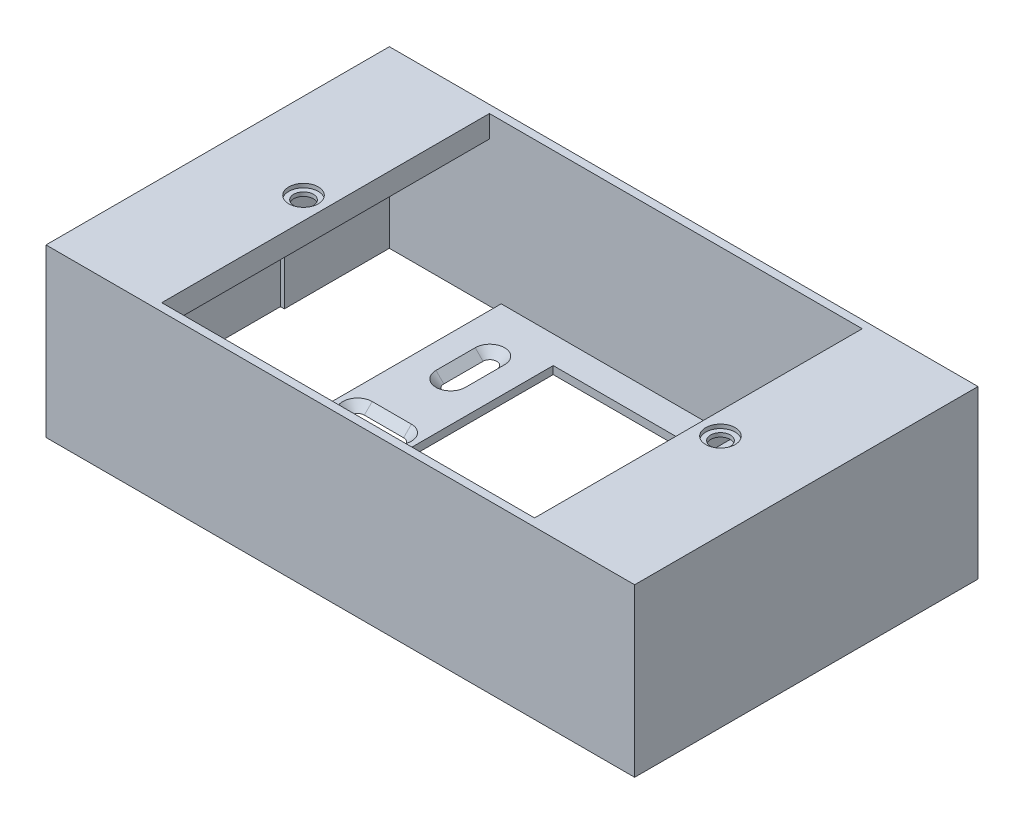
SolidWorks part; units mm, degrees
ref_plane "Front Plane" through (0, 0, 0) normal (0, 0, 1) x (1, 0, 0)
ref_plane "Top Plane" through (0, 0, 0) normal (0, 1, 0) x (1, 0, 0)
ref_plane "Right Plane" through (0, 0, 0) normal (1, 0, 0) x (0, 0, -1)
sketch "Sketch1" plane through (0, 0, 0) normal (0, 1, 0) x (1, 0, 0)
  line L1 (-60, -35) -> (60, -35)
  line L2 (-60, -35) -> (-60, 35)
  line L3 (-60, 35) -> (60, 35)
  line L4 (60, -35) -> (60, 35)
  line L5 (-60, -35) -> (60, 35) construction
  line L6 (-60, 35) -> (60, -35) construction
  point P0 (0, 0)
  dimension "D1" = 120
  dimension "D2" = 70
extrude "Boss-Extrude1" add sketch "Sketch1" along normal blind 34
shell "Shell1" thickness 1.6
sketch "Sketch2" plane through (0, 34, 0) normal (0, 1, 0) x (1, 0, 0)
  line L0 (-60, 35) -> (-60, -35) construction
  line L1 (-38, -33.4) -> (38, -33.4)
  line L2 (-38, -33.4) -> (-38, 33.4)
  line L3 (-38, 33.4) -> (38, 33.4)
  line L4 (38, -33.4) -> (38, 33.4)
  line L5 (-38, -33.4) -> (38, 33.4) construction
  line L6 (-38, 33.4) -> (38, -33.4) construction
  line L7 (60, 35) -> (-60, 35) construction
  point P0 (0, 0)
  dimension "D1" = 22
  dimension "D2" = 1.6
extrude "Cut-Extrude1" cut sketch "Sketch2" against normal up to next
sketch "Sketch3" plane through (0, 34, 0) normal (0, 1, 0) x (1, 0, 0)
  line L0 (-60, 0) -> (60, 0) construction
  line L1 (-60, 35) -> (-60, -35) construction
  line L2 (60, -35) -> (60, 35) construction
  line L3 (60, 35) -> (-60, 35) construction
  line L4 (-39.6, -35) -> (-38, -35)
  line L5 (-39.6, -35) -> (-39.6, 35)
  line L6 (-39.6, 35) -> (-38, 35)
  line L7 (-38, -35) -> (-38, 35)
  line L8 (-39.6, -35) -> (-38, 35) construction
  line L9 (-39.6, 35) -> (-38, -35) construction
  line L10 (-38, 33.4) -> (-38, -33.4) construction
  point P6 (-38.8, 0)
  point P15 (0, 0)
  point P16 (0, 0)
  dimension "D1" = 1.6
extrude "Boss-Extrude2" add sketch "Sketch3" against normal blind 4.5
sketch "Sketch4" plane through (0, 34, 0) normal (0, 1, 0) x (1, 0, 0)
  line L0 (-60, 35) -> (-60, -35) construction
  circle A0 centre (-42.5, 0) radius 3
  point P2 (0, 0)
  dimension "D1" = 6
  dimension "D2" = 17.5
extrude "Cut-Extrude2" cut sketch "Sketch4" against normal blind 0.8
sketch "Sketch5" plane through (0, 34, 0) normal (0, 1, 0) x (1, 0, 0)
  circle A0 centre (-42.5, 0) radius 2
  dimension "D1" = 4
extrude "Cut-Extrude3" cut sketch "Sketch5" against normal up to next contours A0
mirror "Mirror1" about plane through (0, 0, 0) normal (1, 0, 0) of "Boss-Extrude2", "Cut-Extrude2", "Cut-Extrude3"
sketch "Sketch7" plane through (0, 0, 0) normal (0, 1, 0) x (1, 0, 0)
  line L0 (-58.4, -33.4) -> (58.4, -33.4) construction
  line L1 (-35.6, 33.4) -> (35.6, 33.4)
  line L2 (-35.6, 33.4) -> (-35.6, -33.4)
  line L3 (-35.6, -33.4) -> (35.6, -33.4)
  line L4 (35.6, 33.4) -> (35.6, -33.4)
  line L5 (-35.6, 33.4) -> (35.6, -33.4) construction
  line L6 (-35.6, -33.4) -> (35.6, 33.4) construction
  line L7 (-60, 35) -> (-60, -35) construction
  line L8 (-19.4, 27.8) -> (19.4, 27.8)
  line L9 (-19.4, 27.8) -> (-19.4, -27.8)
  line L10 (-19.4, -27.8) -> (19.4, -27.8)
  line L11 (19.4, 27.8) -> (19.4, -27.8)
  line L12 (-19.4, 27.8) -> (19.4, -27.8) construction
  line L13 (-19.4, -27.8) -> (19.4, 27.8) construction
  line L14 (-60, -35) -> (60, -35) construction
  point P0 (0, 0)
  point P8 (0, 0)
  dimension "D1" = 40.6
  dimension "D2" = 16.2
  dimension "D3" = 7.2
extrude "Boss-Extrude3" add sketch "Sketch7" along normal blind 1.6
sketch "Sketch8" plane through (0, 1.6, 0) normal (0, 1, 0) x (1, 0, 0)
  line L0 (-27.5, -33.4) -> (-27.5, 33.4) construction
  line L1 (-38, -33.4) -> (38, -33.4) construction
  line L2 (35.6, 33.4) -> (-35.6, 33.4) construction
  line L3 (27.5, -33.4) -> (27.5, 33.4) construction
  line L4 (-35.6, -33.4) -> (35.6, -33.4) construction
  line L5 (-35.6, 0) -> (35.6, 0) construction
  line L6 (-35.6, 33.4) -> (-35.6, -33.4) construction
  line L7 (35.6, -33.4) -> (35.6, 33.4) construction
  line L8 (-31.5, 0) -> (-23.5, 0) construction
  line L9 (-31.5, 3) -> (-23.5, 3)
  line L10 (-31.5, -3) -> (-23.5, -3)
  line L11 (27.5, -4) -> (27.5, 4) construction
  line L12 (24.5, -4) -> (24.5, 4)
  line L13 (30.5, -4) -> (30.5, 4)
  line L14 (-35.6, 19) -> (35.6, 19) construction
  line L15 (-35.6, -19) -> (35.6, -19) construction
  line L16 (60, 35) -> (-60, 35) construction
  line L17 (-60, -35) -> (60, -35) construction
  line L18 (23.5, 19) -> (31.5, 19) construction
  line L19 (23.5, 22) -> (31.5, 22)
  line L20 (23.5, 16) -> (31.5, 16)
  line L21 (23.5, -19) -> (31.5, -19) construction
  line L22 (23.5, -16) -> (31.5, -16)
  line L23 (23.5, -22) -> (31.5, -22)
  line L24 (-27.5, 15) -> (-27.5, 23) construction
  line L25 (-30.5, 15) -> (-30.5, 23)
  line L26 (-24.5, 15) -> (-24.5, 23)
  line L27 (-27.5, -23) -> (-27.5, -15) construction
  line L28 (-30.5, -23) -> (-30.5, -15)
  line L29 (-24.5, -23) -> (-24.5, -15)
  arc A0 (-31.5, 3) -> (-31.5, -3) centre (-31.5, 0) ccw
  arc A1 (-23.5, -3) -> (-23.5, 3) centre (-23.5, 0) ccw
  arc A2 (24.5, -4) -> (30.5, -4) centre (27.5, -4) ccw
  arc A3 (30.5, 4) -> (24.5, 4) centre (27.5, 4) ccw
  arc A4 (23.5, 22) -> (23.5, 16) centre (23.5, 19) ccw
  arc A5 (31.5, 16) -> (31.5, 22) centre (31.5, 19) ccw
  arc A6 (23.5, -16) -> (23.5, -22) centre (23.5, -19) ccw
  arc A7 (31.5, -22) -> (31.5, -16) centre (31.5, -19) ccw
  arc A8 (-30.5, 15) -> (-24.5, 15) centre (-27.5, 15) ccw
  arc A9 (-24.5, 23) -> (-30.5, 23) centre (-27.5, 23) ccw
  arc A10 (-30.5, -23) -> (-24.5, -23) centre (-27.5, -23) ccw
  arc A11 (-24.5, -15) -> (-30.5, -15) centre (-27.5, -15) ccw
  point P18 (-27.5, 0)
  point P25 (27.5, 0)
  point P40 (27.5, 19)
  point P47 (27.5, -19)
  point P54 (-27.5, 19)
  point P61 (-27.5, -19)
  dimension "D4" = 3
  dimension "D1" = 8.1
  dimension "D2" = 8.1
  dimension "D3" = 8
  dimension "D5" = 16
  dimension "D6" = 16
extrude "Cut-Extrude4" cut sketch "Sketch8" against normal up to next (1.6 mm away) draft 45
sketch "Sketch9" plane through (-60, 0, 0) normal (-1, 0, 0) x (0, 0, 1)
  line L0 (-35, 0) -> (35, 0) construction
  line L1 (-12, 0) -> (12, 0)
  line L2 (-12, 0) -> (-12, 12)
  line L3 (-12, 12) -> (12, 12)
  line L4 (12, 0) -> (12, 12)
  line L5 (-12, 0) -> (12, 12) construction
  line L6 (-12, 12) -> (12, 0) construction
  point P0 (0, 6)
  point P5 (0, 0)
  dimension "D1" = 24
  dimension "D2" = 12
extrude "Cut-Extrude5" cut sketch "Sketch9" along normal blind 0.8 from offset 1.6 offset against normal yes
mirror "Mirror2" about plane through (0, 0, 0) normal (1, 0, 0) of "Cut-Extrude5"
